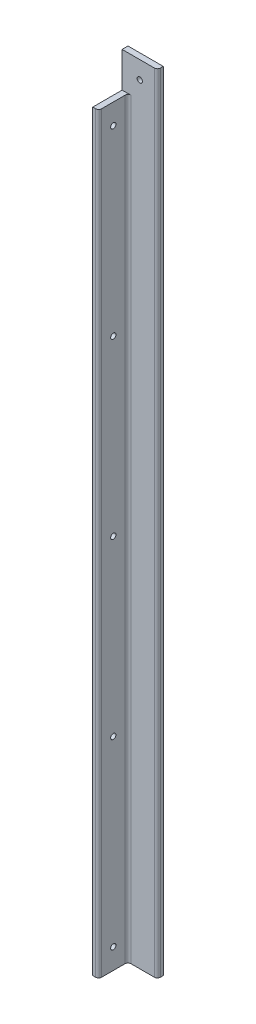
SolidWorks part; units mm, degrees
material "6061 Alloy"
ref_plane "Front Plane" through (0, 0, 0) normal (0, 0, 1) x (1, 0, 0)
ref_plane "Top Plane" through (0, 0, 0) normal (0, 1, 0) x (1, 0, 0)
ref_plane "Right Plane" through (0, 0, 0) normal (1, 0, 0) x (0, 0, -1)
sketch "Sketch2" plane through (0, 0, 0) normal (0, 1, 0) x (1, 0, 0)
  line L0 (0, 0) -> (19.05, 0)
  line L1 (0, 0) -> (0, 19.05)
  line L2 (4.7625, 3.175) -> (17.4625, 3.175)
  line L3 (3.175, 4.7625) -> (3.175, 17.4625)
  line L4 (0, 19.05) -> (1.5875, 19.05)
  line L5 (19.05, 1.5875) -> (19.05, 0)
  line L6 (3.175, 3.175) -> (3.175, 19.05) construction
  line L7 (3.175, 3.175) -> (19.05, 3.175) construction
  arc A0 (3.175, 17.4625) -> (1.5875, 19.05) centre (1.5875, 17.4625) ccw
  arc A1 (3.175, 4.7625) -> (4.7625, 3.175) centre (4.7625, 4.7625) ccw
  arc A2 (17.4625, 3.175) -> (19.05, 1.5875) centre (17.4625, 1.5875) cw
  dimension "D2" = 1.5875
  dimension "D1" = 3.175
extrude "Boss-Extrude1" add sketch "Sketch2" along normal blind 431.8
sketch "Sketch4" plane through (3.175, 0, 0) normal (1, 0, 0) x (0, 0, -1)
  line L0 (19.05, 431.8) -> (19.05, 406.4)
  line L1 (19.05, 431.8) -> (19.05, 0) construction
  line L2 (19.05, 406.4) -> (3.175, 406.4)
  line L3 (3.175, 431.8) -> (3.175, 0) construction
  line L4 (3.175, 406.4) -> (3.175, 431.8)
  line L5 (3.175, 431.8) -> (19.05, 431.8)
extrude "Cut-Extrude1" cut sketch "Sketch4" against normal blind 6.35
sketch "Sketch5" plane through (3.175, 0, 0) normal (-1, 0, 0) x (0, 0, 1)
  line L8 (-4.7625, 406.4) -> (-3.175, 406.4)
  line L9 (-3.175, 406.4) -> (-3.175, 431.8)
  line L10 (-3.175, 431.8) -> (-4.7625, 431.8)
  line L11 (-4.7625, 431.8) -> (-4.7625, 406.4)
  line L12 (-4.7625, 406.4) -> (-3.175, 406.4)
  line L13 (-3.175, 406.4) -> (-3.175, 431.8)
  line L14 (-3.175, 431.8) -> (-4.7625, 431.8)
  line L15 (-4.7625, 431.8) -> (-4.7625, 406.4)
  dimension "D1" = 0
extrude "Cut-Extrude2" cut sketch "Sketch5" against normal blind 6.35
sketch "Sketch6" plane through (3.175, 0, 0) normal (1, 0, 0) x (0, 0, -1)
  line L0 (19.05, 0) -> (3.175, 0) construction
  line L1 (11.1125, 0) -> (11.1125, 15.875) construction
  line L2 (19.05, 406.4) -> (3.175, 406.4) construction
  line L3 (11.1125, 406.4) -> (11.1125, 390.525) construction
  line L4 (11.1125, 15.875) -> (11.1125, 203.2) construction
  line L5 (11.1125, 203.2) -> (11.1125, 390.525) construction
  circle A1 centre (11.1125, 109.5375) radius 1.4224
  circle A2 centre (11.1125, 203.2) radius 1.4224
  circle A3 centre (11.1125, 296.8625) radius 1.4224
  circle A5 centre (11.1125, 11.1125) radius 1.4224
  circle A6 centre (11.1125, 395.2875) radius 1.4224
  point P12 (11.1125, 203.2)
  point P13 (11.1125, 296.8625)
  point P15 (11.1125, 109.5375)
  dimension "D2" = 2.8448
  dimension "D3" = 2.8448
  dimension "D4" = 2.8448
  dimension "D6" = 2.8448
  dimension "D7" = 2.8448
extrude "Cut-Extrude3" cut sketch "Sketch6" against normal blind 5.08
sketch "Sketch7" plane through (0, 431.8, 0) normal (0, 1, 0) x (1, 0, 0)
  line L8 (17.4625, 3.175) -> (0, 3.175)
  line L9 (0, 3.175) -> (0, 0)
  line L10 (0, 0) -> (19.05, 0)
  line L11 (19.05, 0) -> (19.05, 1.5875)
  line L12 (17.4625, 3.175) -> (0, 3.175)
  line L13 (0, 3.175) -> (0, 0)
  line L14 (0, 0) -> (19.05, 0)
  line L15 (19.05, 0) -> (19.05, 1.5875)
  arc A2 (19.05, 1.5875) -> (17.4625, 3.175) centre (17.4625, 1.5875) ccw
  arc A3 (19.05, 1.5875) -> (17.4625, 3.175) centre (17.4625, 1.5875) ccw
  dimension "D1" = 0
extrude "Cut-Extrude4" cut sketch "Sketch7" against normal blind 6.35
sketch "Sketch8" plane through (0, 0, -3.175) normal (0, 0, -1) x (-1, 0, 0)
  line L0 (0, 425.45) -> (0, 415.925) construction
  line L1 (0, 425.45) -> (0, 406.4) construction
  line L2 (0, 415.925) -> (-9.525, 415.925) construction
  circle A0 centre (-9.525, 415.925) radius 1.4224
  dimension "D1" = 2.8448
extrude "Cut-Extrude5" cut sketch "Sketch8" against normal blind 5.08
ref_plane "Plane1" through (0, 0, 2.54) normal (0, 0, 1) x (1, 0, 0)
mirror "Mirror3" about plane through (0, 0, 2.54) normal (0, 0, 1) of bodies 106
sketch "Sketch9" plane through (0, 0, 2.54) normal (0, 0, 1) x (1, 0, 0)
  line L1 (-6.6248, 469.5409) -> (22.2362, 469.5409)
  line L2 (-6.6248, 469.5409) -> (-6.6248, -77.9837)
  line L3 (-6.6248, -77.9837) -> (22.2362, -77.9837)
  line L4 (22.2362, 469.5409) -> (22.2362, -77.9837)
extrude "Cut-Extrude6" cut sketch "Sketch9" against normal blind 30.48
